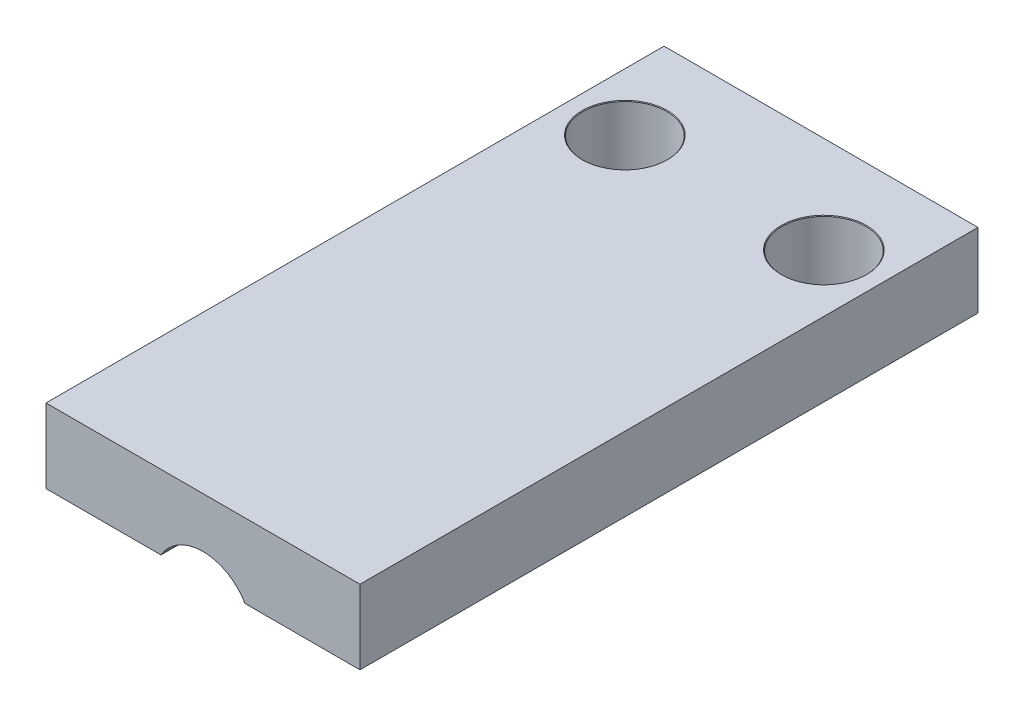
SolidWorks part; units mm, degrees
ref_plane "Front Plane" through (0, 0, 0) normal (0, 0, 1) x (1, 0, 0)
ref_plane "Top Plane" through (0, 0, 0) normal (0, 1, 0) x (1, 0, 0)
ref_plane "Right Plane" through (0, 0, 0) normal (1, 0, 0) x (0, 0, -1)
sketch "Sketch1" plane through (0, 0, 0) normal (0, 1, 0) x (1, 0, 0)
  line L1 (-6.35, 12.5) -> (6.35, 12.5)
  line L2 (-6.35, 12.5) -> (-6.35, -12.5)
  line L3 (-6.35, -12.5) -> (6.35, -12.5)
  line L4 (6.35, 12.5) -> (6.35, -12.5)
  line L5 (-6.35, 12.5) -> (6.35, -12.5) construction
  line L6 (-6.35, -12.5) -> (6.35, 12.5) construction
  point P0 (0, 0)
  dimension "D1" = 25
  dimension "D2" = 12.7
extrude "Boss-Extrude1" add sketch "Sketch1" along normal blind 3
sketch "Sketch2" plane through (0, 0, 12.5) normal (0, 0, 1) x (1, 0, 0)
  line L0 (-6.35, 0) -> (6.35, 0) construction
  arc A0 (-1.7, 0) -> (1.7, 0) centre (0, -1) cw
  point P3 (0, 0)
  point P7 (1.7, 0)
  dimension "D1" = 1.7
  dimension "D2" = 1
extrude "Cut-Extrude1" cut sketch "Sketch2" against normal blind 17.18 and the other way through all flip side to cut
hole_wizard "M3 Clearance Hole1" positions "Sketch10" profile "Sketch9" hole size "M3" standard "ANSI Metric"
sketch "Sketch10" plane through (0, 3, 0) normal (0, 1, 0) x (1, 0, 0)
  line L0 (-4.025, 8.59) -> (4.025, 8.59) construction
  line L2 (6.35, 12.5) -> (-6.35, 12.5) construction
  point P0 (-4.025, 8.59)
  point P2 (4.025, 8.59)
  point P11 (0, 8.59)
  dimension "D1" = 8.05
  dimension "D2" = 3.91
sketch "Sketch9" plane through (-4.025, 3, -8.59) normal (1, 0, 0) x (0, 0, 1)
  line L0 (0, 0) -> (0, 4.0215)
  line L1 (0, 4.0215) -> (1.7, 3)
  line L2 (1.7, 3) -> (1.7, 0.025)
  line L3 (1.7, 0.025) -> (1.725, 0)
  line L5 (1.725, 0) -> (0, 0)
  line L6 (-1.7, 0.025) -> (-1.725, 0) construction
  line L10 (0, 4.0215) -> (-1.7, 3) construction
  line L11 (0, -6.35) -> (0, 107.95) construction
  dimension "Hole Dia." = 3.4
  dimension "Hole Depth" = 3
  dimension "Near C'Sink Dia." = 3.45
  dimension "Near C'Sink Angle" = 90
  dimension "Drill Angle" = 118
